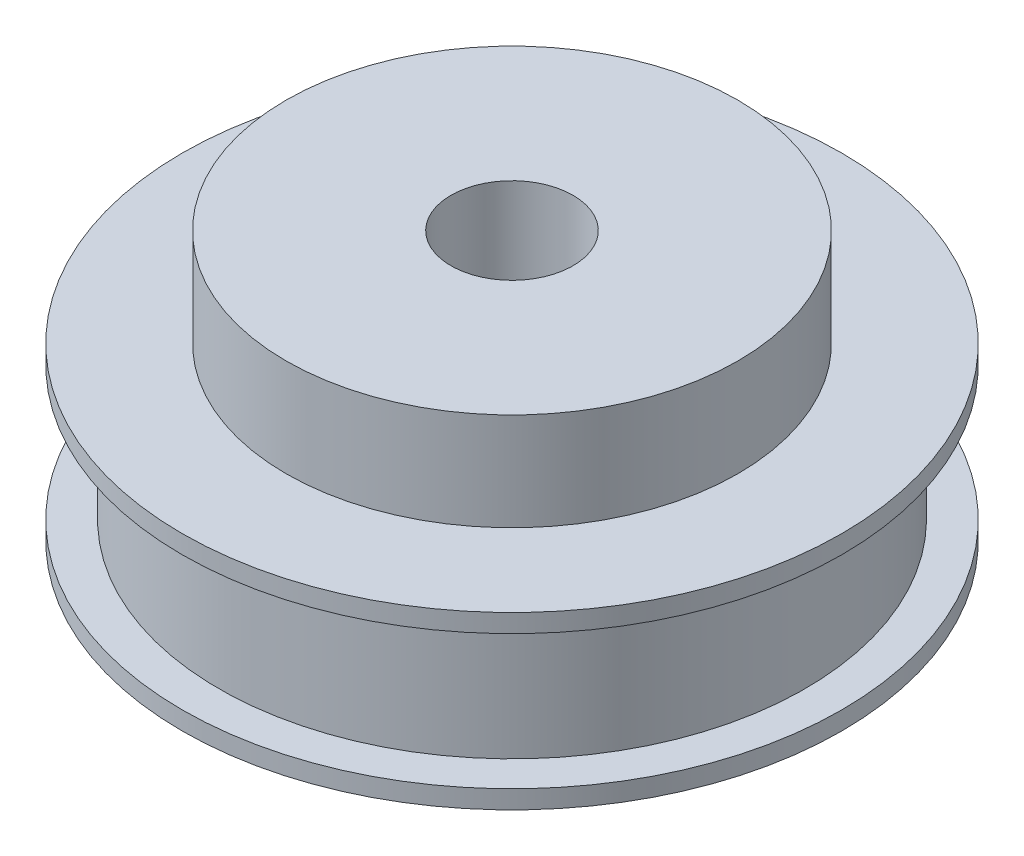
SolidWorks part; units mm, degrees
ref_plane "Face" through (0, 0, 0) normal (0, 0, 1) x (1, 0, 0)
ref_plane "Dessus" through (0, 0, 0) normal (0, 1, 0) x (1, 0, 0)
ref_plane "Droite" through (0, 0, 0) normal (1, 0, 0) x (0, 0, -1)
sketch "Esquisse1" plane through (0, 0, 0) normal (0, 0, 1) x (1, 0, 0)
  line L0 (5, 0) -> (27, 0)
  line L1 (27, 0) -> (27, 1.5)
  line L2 (27, 1.5) -> (24, 1.5)
  line L3 (24, 1.5) -> (24, 12.5)
  line L4 (24, 12.5) -> (27, 12.5)
  line L5 (27, 12.5) -> (27, 14)
  line L6 (27, 14) -> (18.5, 14)
  line L7 (18.5, 14) -> (18.5, 22)
  line L8 (18.5, 22) -> (5, 22)
  line L9 (5, 22) -> (5, 0)
  line L10 (0, 0) -> (0, 33.3036) construction
  dimension "D1" = 10
  dimension "D2" = 54
  dimension "D3" = 11
  dimension "D4" = 1.5
  dimension "D5" = 3
  dimension "D6" = 22
  dimension "D7" = 37
revolve "Révolution1" add sketch "Esquisse1" angle 360 about L10
